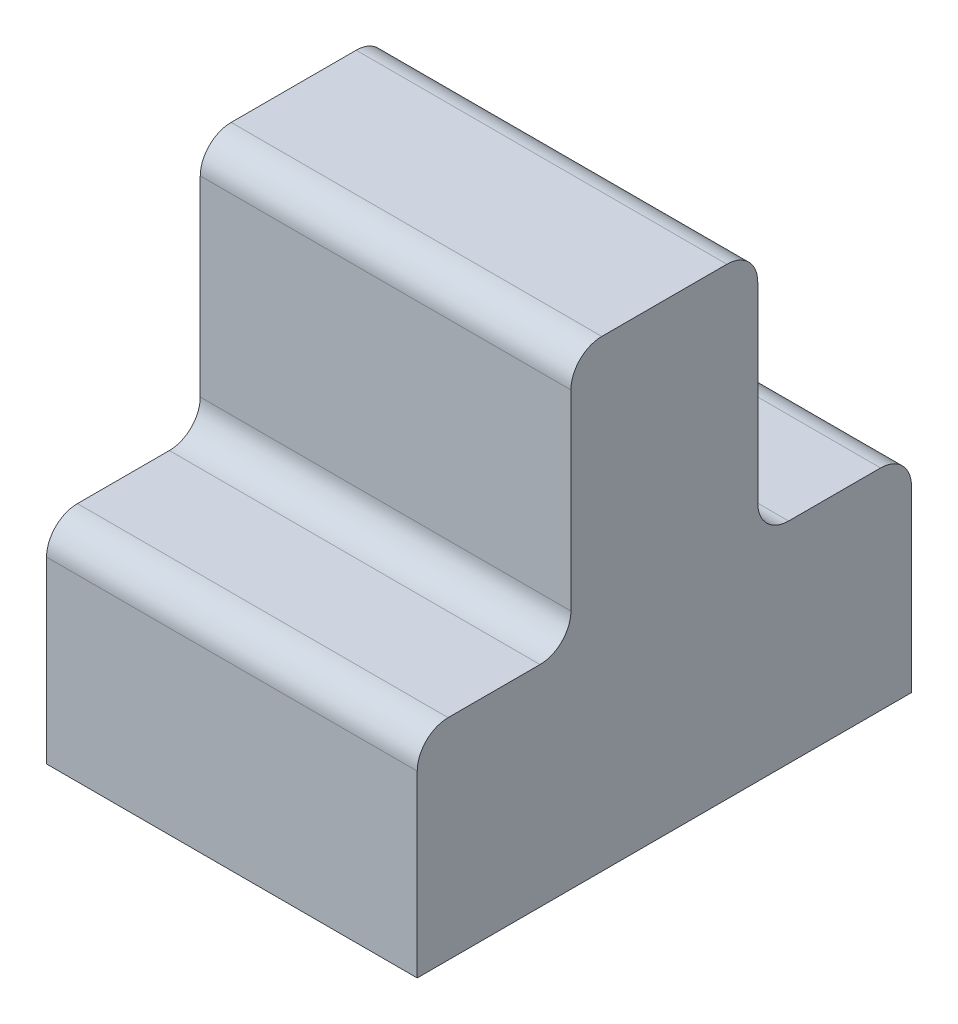
SolidWorks part; units mm, degrees
ref_plane "Front Plane" through (0, 0, 0) normal (0, 0, 1) x (1, 0, 0)
ref_plane "Top Plane" through (0, 0, 0) normal (0, 1, 0) x (1, 0, 0)
ref_plane "Right Plane" through (0, 0, 0) normal (1, 0, 0) x (0, 0, -1)
sketch "Sketch1" plane through (0, 0, 0) normal (1, 0, 0) x (0, 0, -1)
  line L1 (0, 0) -> (8, 0)
  line L2 (0, 0) -> (0, 15)
  line L3 (0, 15) -> (8, 15)
  line L4 (8, 0) -> (8, 15)
  line L5 (0, 15) -> (4.9756, 15)
  line L6 (0, 15) -> (0, 6.8005)
  line L7 (0, 6.8005) -> (4.9756, 6.8005)
  line L8 (4.9756, 15) -> (4.9756, 6.8005)
  point P8 (5.1413, 6.3035)
  point P9 (4.9756, 6.8005)
  dimension "D1" = 15
  dimension "D2" = 8
extrude "Boss-Extrude1" add sketch "Sketch1" along normal blind 12 contours L3 L8 L7 L2 L1 L4
fillet "Fillet1" radius 1 3 edges at (6, 6.8005, 0) (6, 6.8005, -4.9756) (6, 15, -4.9756)
mirror "Mirror2" about plane through (12, 0, -8) normal (0, 0, 1) of "Fillet1", "Boss-Extrude1"
